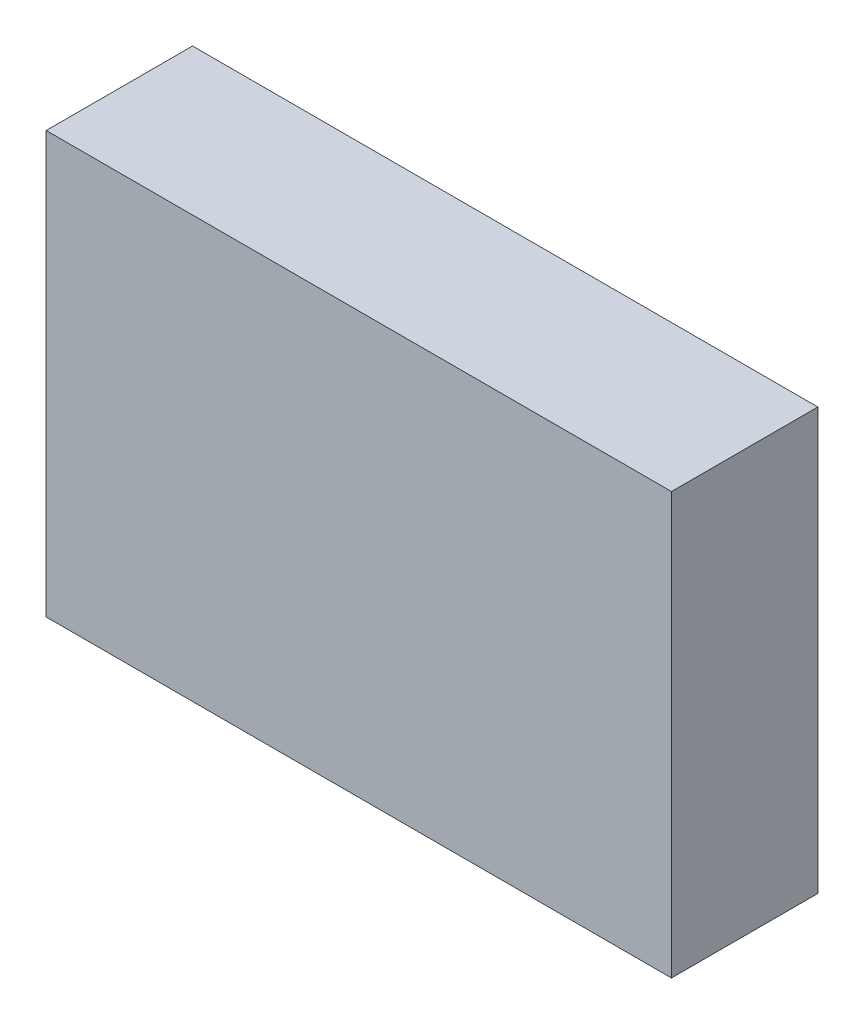
SolidWorks part; units mm, degrees
ref_plane "前视基准面" through (0, 0, 0) normal (0, 0, 1) x (1, 0, 0)
ref_plane "上视基准面" through (0, 0, 0) normal (0, 1, 0) x (1, 0, 0)
ref_plane "右视基准面" through (0, 0, 0) normal (1, 0, 0) x (0, 0, -1)
sketch "草图1" plane through (0, 0, 0) normal (0, 0, 1) x (1, 0, 0)
  line L0 (-3.525, -2.625) -> (3.525, -2.625)
  line L1 (3.525, -2.625) -> (3.525, 2.125)
  line L2 (3.525, 2.125) -> (-3.525, 2.125)
  line L3 (-3.525, 2.125) -> (-3.525, -2.625)
extrude "凸台-拉伸1" add sketch "草图1" along normal blind 1.65 from offset 0
